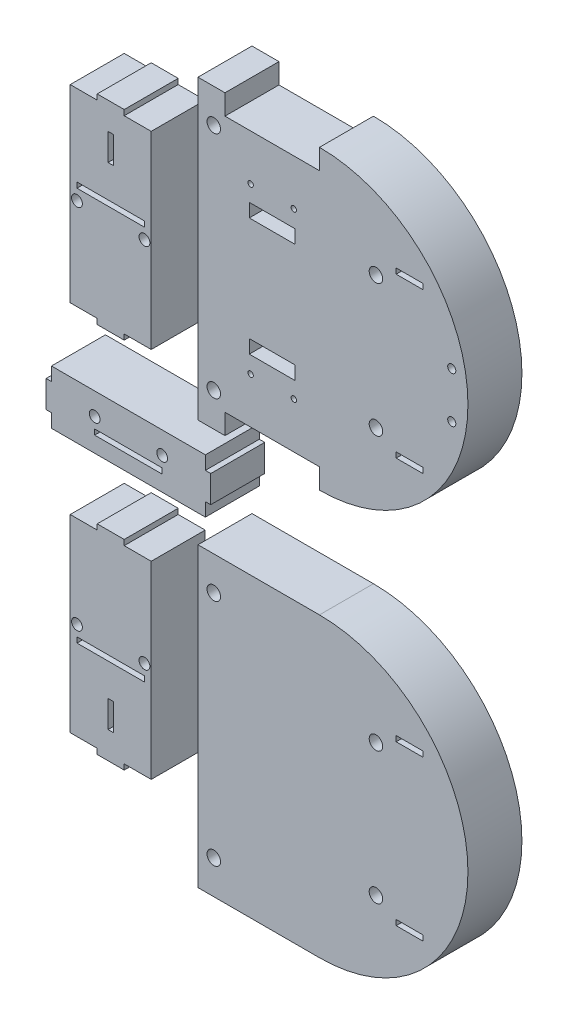
SolidWorks part; units mm, degrees
ref_plane "Front Plane" through (0, 0, 0) normal (0, 0, 1) x (1, 0, 0)
ref_plane "Top Plane" through (0, 0, 0) normal (0, 1, 0) x (1, 0, 0)
ref_plane "Right Plane" through (0, 0, 0) normal (1, 0, 0) x (0, 0, -1)
sketch "Sketch1" plane through (0, 0, 0) normal (0, 0, 1) x (1, 0, 0)
  line L0 (-47.0823, 60.1115) -> (-47.0823, -49.8885)
  line L1 (-47.0823, 60.1115) -> (-37.0823, 60.1115)
  line L3 (-47.0823, -49.8885) -> (-37.0823, -49.8885)
  line L5 (-37.0823, 60.1115) -> (-37.0823, 52.6115)
  line L6 (-37.0823, 52.6115) -> (-2.0823, 52.6115)
  line L7 (-2.0823, 52.6115) -> (-2.0823, 60.1115)
  line L8 (-2.0823, -42.3885) -> (-2.0823, -49.8885)
  line L11 (-37.0823, -42.3885) -> (-2.0823, -42.3885)
  line L12 (-19.5823, 29.4593) -> (-28.0823, 29.4593)
  line L14 (-19.5823, 29.4593) -> (-11.0823, 29.4593)
  line L16 (-11.0823, 29.4593) -> (-11.0823, 24.4593)
  line L17 (-11.0823, 24.4593) -> (-28.0823, 24.4593)
  line L18 (-28.0823, 24.4593) -> (-28.0823, 29.4593)
  line L19 (-37.0823, -49.8885) -> (-37.0823, -42.3885)
  line L20 (36.337, 35.6115) -> (26.337, 35.6115)
  line L21 (26.337, 35.6115) -> (26.337, 33.6115)
  line L22 (26.337, 33.6115) -> (36.337, 33.6115)
  line L23 (36.337, 33.6115) -> (36.337, 35.6115)
  line L24 (36.337, -23.3885) -> (36.337, -25.3885)
  line L25 (36.337, -25.3885) -> (26.337, -25.3885)
  line L26 (26.337, -25.3885) -> (26.337, -23.3885)
  line L27 (26.337, -23.3885) -> (36.337, -23.3885)
  line L28 (-28.0823, -14.2362) -> (-28.0823, -19.2362)
  line L29 (-11.0823, -14.2362) -> (-28.0823, -14.2362)
  line L30 (-11.0823, -19.2362) -> (-11.0823, -14.2362)
  line L31 (-19.5823, -19.2362) -> (-11.0823, -19.2362)
  line L32 (-19.5823, -19.2362) -> (-28.0823, -19.2362)
  line L33 (-94.4124, -103.8484) -> (-94.4124, -173.8484)
  line L34 (-94.4124, -173.8484) -> (-84.4124, -173.8484)
  line L35 (-64.4124, -173.8484) -> (-64.4124, -103.8484)
  line L41 (26.337, -116.3885) -> (36.337, -116.3885)
  line L42 (26.337, -114.3885) -> (26.337, -116.3885)
  line L43 (36.337, -114.3885) -> (26.337, -114.3885)
  line L44 (36.337, -116.3885) -> (36.337, -114.3885)
  line L45 (36.337, -173.3885) -> (36.337, -175.3885)
  line L46 (26.337, -173.3885) -> (36.337, -173.3885)
  line L47 (26.337, -175.3885) -> (26.337, -173.3885)
  line L48 (36.337, -175.3885) -> (26.337, -175.3885)
  line L60 (-47.0823, -89.8885) -> (-37.0823, -89.8885)
  line L61 (-47.0823, -199.8885) -> (-47.0823, -89.8885)
  line L62 (-47.0823, -199.8885) -> (-37.0823, -199.8885)
  line L63 (-37.0823, -199.8885) -> (-2.0823, -199.8885)
  line L64 (-37.0823, -89.8885) -> (-2.0823, -89.8885)
  line L65 (-64.4124, -103.8484) -> (-74.4124, -103.8484)
  line L66 (-84.4124, -103.8484) -> (-84.4124, -101.8484)
  line L67 (-84.4124, -101.8484) -> (-74.4124, -101.8484)
  line L68 (-74.4124, -101.8484) -> (-74.4124, -103.8484)
  line L69 (-84.4124, -173.8484) -> (-84.4124, -175.8484)
  line L70 (-84.4124, -175.8484) -> (-74.4124, -175.8484)
  line L71 (-74.4124, -175.8484) -> (-74.4124, -173.8484)
  line L76 (-84.4124, -103.8484) -> (-94.4124, -103.8484)
  line L77 (-74.4124, -173.8484) -> (-64.4124, -173.8484)
  line L78 (-101.3572, -59.6793) -> (-44.3572, -59.6793)
  line L79 (-44.3572, -59.6793) -> (-44.3572, -64.6793)
  line L80 (-91.9124, -143.8484) -> (-66.9124, -143.8484)
  line L81 (-91.9124, -143.8484) -> (-91.9124, -141.8484)
  line L82 (-91.9124, -141.8484) -> (-66.9124, -141.8484)
  line L83 (-66.9124, -141.8484) -> (-66.9124, -143.8484)
  line L100 (-66.9124, 2.0715) -> (-66.9124, 4.0715)
  line L101 (-91.9124, 2.0715) -> (-66.9124, 2.0715)
  line L102 (-91.9124, 4.0715) -> (-91.9124, 2.0715)
  line L103 (-91.9124, 4.0715) -> (-66.9124, 4.0715)
  line L104 (-74.4124, 34.0715) -> (-64.4124, 34.0715)
  line L105 (-84.4124, -35.9285) -> (-94.4124, -35.9285)
  line L106 (-74.4124, 36.0715) -> (-74.4124, 34.0715)
  line L107 (-84.4124, 36.0715) -> (-74.4124, 36.0715)
  line L108 (-84.4124, 34.0715) -> (-84.4124, 36.0715)
  line L109 (-74.4124, -37.9285) -> (-74.4124, -35.9285)
  line L110 (-84.4124, -37.9285) -> (-74.4124, -37.9285)
  line L111 (-84.4124, -35.9285) -> (-84.4124, -37.9285)
  line L112 (-64.4124, -35.9285) -> (-74.4124, -35.9285)
  line L113 (-64.4124, 34.0715) -> (-64.4124, -35.9285)
  line L114 (-94.4124, 34.0715) -> (-84.4124, 34.0715)
  line L115 (-94.4124, -35.9285) -> (-94.4124, 34.0715)
  line L116 (-44.3572, -79.6793) -> (-101.3572, -79.6793)
  line L117 (-101.3572, -79.6793) -> (-101.3572, -74.6793)
  line L118 (-85.3572, -73.867) -> (-60.3572, -73.867)
  line L119 (-60.3572, -73.867) -> (-60.3572, -71.867)
  line L120 (-80.4124, -155.8484) -> (-80.4124, -165.8484)
  line L121 (-80.4124, -165.8484) -> (-78.4124, -165.8484)
  line L122 (-78.4124, -165.8484) -> (-78.4124, -155.8484)
  line L123 (-78.4124, -155.8484) -> (-80.4124, -155.8484)
  line L124 (-80.4124, 26.0715) -> (-78.4124, 26.0715)
  line L125 (-78.4124, 26.0715) -> (-78.4124, 16.0715)
  line L126 (-80.4124, 16.0715) -> (-80.4124, 26.0715)
  line L127 (-78.4124, 16.0715) -> (-80.4124, 16.0715)
  line L128 (-60.3572, -71.867) -> (-85.3572, -71.867)
  line L129 (-85.3572, -71.867) -> (-85.3572, -73.867)
  line L130 (-44.3572, -64.6793) -> (-42.3572, -64.6793)
  line L131 (-42.3572, -64.6793) -> (-42.3572, -74.6793)
  line L132 (-42.3572, -74.6793) -> (-44.3572, -74.6793)
  line L133 (-101.3572, -64.6793) -> (-103.3572, -64.6793)
  line L134 (-103.3572, -64.6793) -> (-103.3572, -74.6793)
  line L135 (-103.3572, -74.6793) -> (-101.3572, -74.6793)
  line L136 (-101.3572, -64.6793) -> (-101.3572, -59.6793)
  line L137 (-44.3572, -74.6793) -> (-44.3572, -79.6793)
  arc A0 (-2.0823, -49.8885) -> (-2.0823, 60.1115) centre (-2.0823, 5.1115) ccw
  circle A1 centre (-27.5823, 35.6115) radius 1
  circle A2 centre (-11.5823, 35.6115) radius 1
  circle A3 centre (46.9218, 13.6115) radius 1.5
  circle A4 centre (-41.2261, 47.6115) radius 2.5
  circle A5 centre (46.9218, -3.3885) radius 1.5
  circle A6 centre (-11.5823, -25.3885) radius 1
  circle A7 centre (-27.5823, -25.3885) radius 1
  circle A8 centre (-41.2261, -37.3885) radius 2.5
  circle A9 centre (18.837, 29.6115) radius 2.5
  circle A10 centre (18.837, -19.3885) radius 2.5
  circle A11 centre (18.837, -120.3885) radius 2.5
  circle A12 centre (18.837, -169.3885) radius 2.5
  circle A13 centre (-41.2261, -102.3885) radius 2.5
  circle A17 centre (-41.2261, -187.3885) radius 2.5
  arc A21 (-2.0823, -89.8885) -> (-2.0823, -199.8885) centre (-2.0823, -144.8885) cw
  circle A24 centre (-66.9124, -137.8484) radius 2
  circle A28 centre (-91.9124, -137.8484) radius 2
  circle A29 centre (-91.9124, -1.9285) radius 2
  circle A30 centre (-66.9124, -1.9285) radius 2
  circle A31 centre (-60.3572, -67.867) radius 2
  circle A32 centre (-85.3572, -67.867) radius 2
  point P71 (-94.4124, -138.8484)
  dimension "D8" = 17
  dimension "D10" = 12.5
  dimension "D6" = 10
  dimension "D15" = 2.5
  dimension "D14" = 4
  dimension "D17" = 4
  dimension "D25" = 5
  dimension "D2" = 35
  dimension "D3" = 7.5
  dimension "D4" = 110
  dimension "D5" = 45
  dimension "D7" = 16
  dimension "D9" = 5
  dimension "D11" = 10
  dimension "D12" = 10
  dimension "D13" = 2.5
  dimension "D16" = 30
  dimension "D18" = 57
  dimension "D19" = 14
  dimension "D20" = 10
  dimension "D21" = 16
  dimension "D22" = 25
  dimension "D23" = 20
  dimension "D24" = 16
  dimension "D26" = 10
  dimension "D27" = 5
extrude "Boss-Extrude2" add sketch "Sketch1" along normal blind 20
